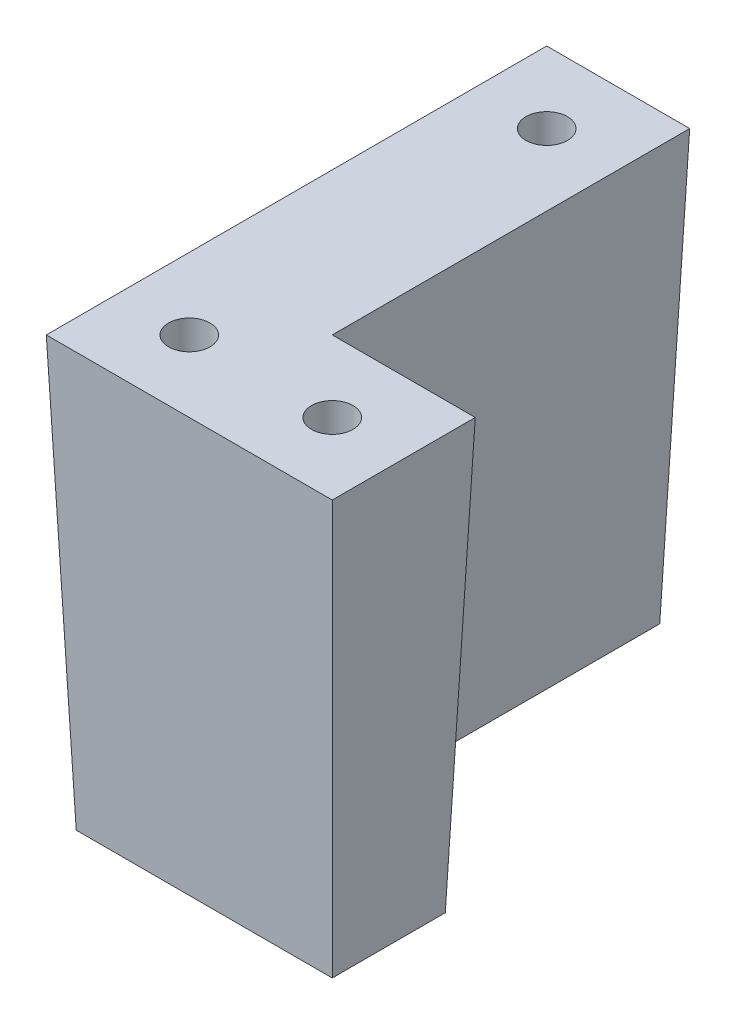
SolidWorks part; units mm, degrees
ref_plane "Front Plane" through (0, 0, 0) normal (0, 0, 1) x (1, 0, 0)
ref_plane "Top Plane" through (0, 0, 0) normal (0, 1, 0) x (1, 0, 0)
ref_plane "Right Plane" through (0, 0, 0) normal (1, 0, 0) x (0, 0, -1)
sketch "Sketch1" plane through (0, 0, 0) normal (0, 1, 0) x (1, 0, 0)
  line L0 (-960, 10) -> (49040, 10) construction
  line L1 (0, 0) -> (40, 0)
  line L2 (0, 0) -> (0, 70)
  line L3 (0, 70) -> (20, 70)
  line L4 (40, 0) -> (40, 20)
  line L7 (40, 20) -> (20, 20)
  line L8 (20, 70) -> (20, 20)
  line L9 (10, -930) -> (10, 49070) construction
  point P10 (40, 10)
  point P13 (10, 70)
  dimension "D1" = 70
  dimension "D2" = 40
  dimension "D3" = 20
  dimension "D4" = 20
extrude "Boss-Extrude1" add sketch "Sketch1" against normal blind 60 draft 2
hole_wizard "CBORE for M5 SBHCS2" positions "Sketch4" profile "Sketch5" counterbore size "M5" standard "ANSI Metric" end condition through all
sketch "Sketch4" plane through (0, -60, 0) normal (0, -1, 0) x (-1, 0, 0)
  line L0 (200960, 10) -> (-249040, 10) construction
  line L1 (-10, -200930) -> (-10, 249070) construction
  line L2 (-40, 0) -> (-40, 20) construction
  line L3 (0, 70) -> (-20, 70) construction
  point P0 (-30, 10)
  point P4 (-10, 10)
  point P8 (-10, 60)
  dimension "D1" = 10
  dimension "D2" = 10
sketch "Sketch5" plane through (30, -60, -10) normal (1, 0, 0) x (0, 0, -1)
  line L0 (0, 0) -> (0, 60)
  line L1 (0, 60) -> (2.9, 60)
  line L3 (2.9, 60) -> (2.9, 55)
  line L4 (2.9, 55) -> (5.75, 55)
  line L5 (5.75, 55) -> (5.75, 0)
  line L7 (5.75, 0) -> (0, 0)
  line L11 (0, -6.35) -> (0, 107.95) construction
  dimension "Thru Hole Dia." = 5.8
  dimension "Thru Hole Depth" = 60
  dimension "C'Bore Dia." = 11.5
  dimension "C'Bore Depth" = 55
